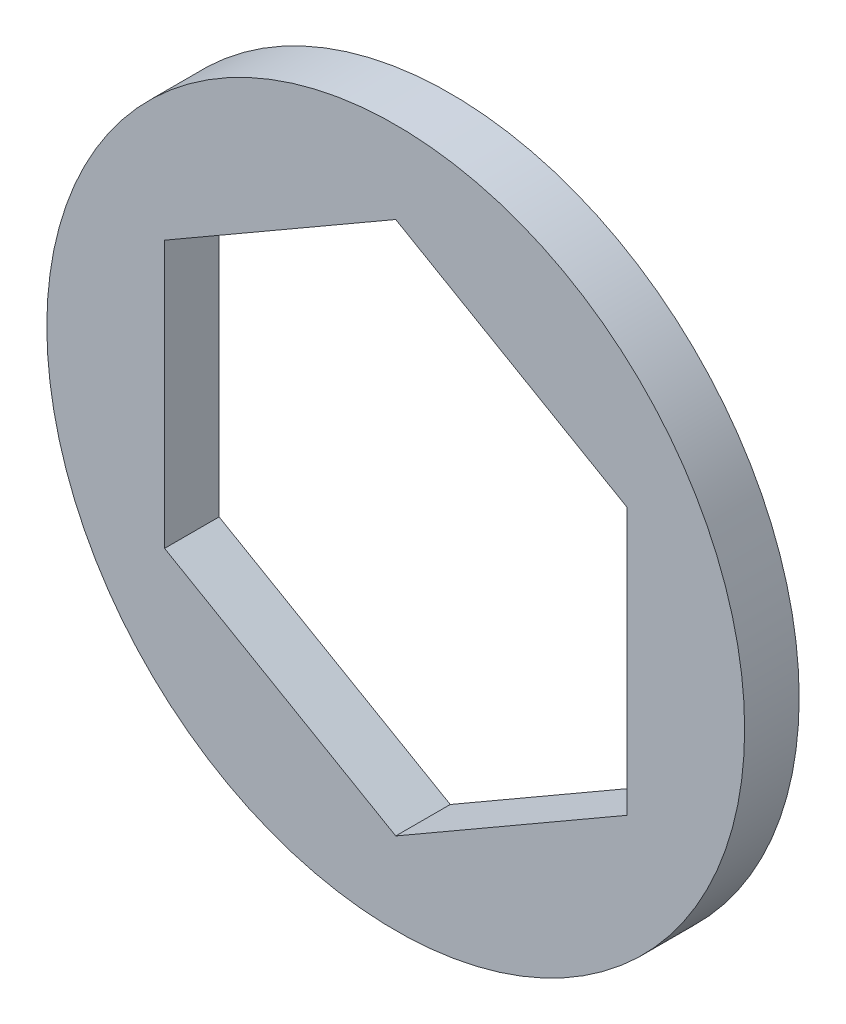
SolidWorks part; units mm, degrees
material "Nylon 101"
ref_plane "Front Plane" through (0, 0, 0) normal (0, 0, 1) x (1, 0, 0)
ref_plane "Top Plane" through (0, 0, 0) normal (0, 1, 0) x (1, 0, 0)
ref_plane "Right Plane" through (0, 0, 0) normal (1, 0, 0) x (0, 0, -1)
sketch "Sketch1" plane through (0, 0, 0) normal (0, 0, 1) x (1, 0, 0)
  line L1 (6.731, 3.8861) -> (0, 7.7723)
  line L2 (0, 7.7723) -> (-6.731, 3.8861)
  line L3 (-6.731, 3.8861) -> (-6.731, -3.8861)
  line L4 (-6.731, -3.8861) -> (0, -7.7723)
  line L5 (0, -7.7723) -> (6.731, -3.8861)
  line L6 (6.731, -3.8861) -> (6.731, 3.8861)
  circle A0 centre (0, 0) radius 6.731 construction
  circle A1 centre (0, 0) radius 10.16
  dimension "D1" = 13.462
  dimension "D2" = 20.32
extrude "Boss-Extrude1" add sketch "Sketch1" along normal blind 1.5875
